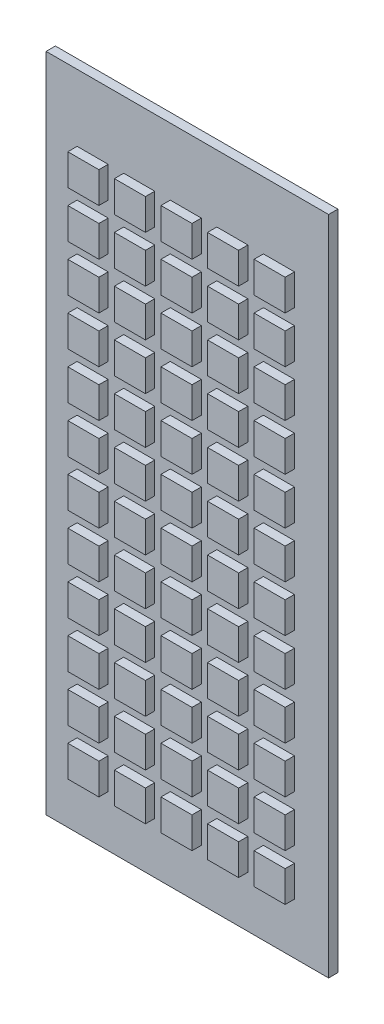
SolidWorks part; units mm, degrees
ref_plane "Alzado" through (0, 0, 0) normal (0, 0, 1) x (1, 0, 0)
ref_plane "Planta" through (0, 0, 0) normal (0, 1, 0) x (1, 0, 0)
ref_plane "Vista lateral" through (0, 0, 0) normal (1, 0, 0) x (0, 0, -1)
sketch "Croquis1" plane through (0, 0, 0) normal (0, 0, 1) x (1, 0, 0)
  line L1 (-455, -1065) -> (455, -1065)
  line L2 (-455, -1065) -> (-455, 1065)
  line L3 (-455, 1065) -> (455, 1065)
  line L4 (455, -1065) -> (455, 1065)
  line L5 (-455, -1065) -> (455, 1065) construction
  line L6 (-455, 1065) -> (455, -1065) construction
  point P0 (0, 0)
  dimension "D1" = 2130
  dimension "D2" = 910
extrude "Saliente-Extruir1" add sketch "Croquis1" along normal blind 30
sketch "Croquis2" plane through (0, 0, 30) normal (0, 0, 1) x (1, 0, 0)
  line L0 (-455, 1065) -> (-455, -1065) construction
  line L1 (-355, 850) -> (-255, 850)
  line L2 (-355, 850) -> (-355, 750)
  line L3 (-355, 750) -> (-255, 750)
  line L4 (-255, 850) -> (-255, 750)
  line L5 (-355, 850) -> (-255, 750) construction
  line L6 (-355, 750) -> (-255, 850) construction
  line L7 (-205, 850) -> (-105, 850)
  line L8 (-205, 850) -> (-205, 750)
  line L9 (-205, 750) -> (-105, 750)
  line L10 (-105, 850) -> (-105, 750)
  line L11 (-205, 850) -> (-105, 750) construction
  line L12 (-205, 750) -> (-105, 850) construction
  line L13 (-55, 850) -> (45, 850)
  line L14 (-55, 850) -> (-55, 750)
  line L15 (-55, 750) -> (45, 750)
  line L16 (45, 850) -> (45, 750)
  line L17 (-55, 850) -> (45, 750) construction
  line L18 (-55, 750) -> (45, 850) construction
  line L19 (95, 850) -> (195, 850)
  line L20 (95, 850) -> (95, 750)
  line L21 (95, 750) -> (195, 750)
  line L22 (195, 850) -> (195, 750)
  line L23 (95, 850) -> (195, 750) construction
  line L24 (95, 750) -> (195, 850) construction
  line L25 (245, 850) -> (345, 850)
  line L26 (245, 850) -> (245, 750)
  line L27 (245, 750) -> (345, 750)
  line L28 (345, 850) -> (345, 750)
  line L29 (245, 850) -> (345, 750) construction
  line L30 (245, 750) -> (345, 850) construction
  line L31 (-205, 700) -> (-105, 700)
  line L32 (-205, 700) -> (-205, 600)
  line L33 (-205, 600) -> (-105, 600)
  line L34 (-105, 700) -> (-105, 600)
  line L35 (-205, 700) -> (-105, 600) construction
  line L36 (-205, 600) -> (-105, 700) construction
  line L37 (-55, 700) -> (45, 700)
  line L38 (-55, 700) -> (-55, 600)
  line L39 (-55, 600) -> (45, 600)
  line L40 (45, 700) -> (45, 600)
  line L41 (-55, 700) -> (45, 600) construction
  line L42 (-55, 600) -> (45, 700) construction
  line L43 (95, 700) -> (195, 700)
  line L44 (95, 700) -> (95, 600)
  line L45 (95, 600) -> (195, 600)
  line L46 (195, 700) -> (195, 600)
  line L47 (95, 700) -> (195, 600) construction
  line L48 (95, 600) -> (195, 700) construction
  line L49 (245, 700) -> (345, 700)
  line L50 (245, 700) -> (245, 600)
  line L51 (245, 600) -> (345, 600)
  line L52 (345, 700) -> (345, 600)
  line L53 (245, 700) -> (345, 600) construction
  line L54 (245, 600) -> (345, 700) construction
  line L55 (-205, 550) -> (-105, 550)
  line L56 (-205, 550) -> (-205, 450)
  line L57 (-205, 450) -> (-105, 450)
  line L58 (-105, 550) -> (-105, 450)
  line L59 (-205, 550) -> (-105, 450) construction
  line L60 (-205, 450) -> (-105, 550) construction
  line L61 (-55, 550) -> (45, 550)
  line L62 (-55, 550) -> (-55, 450)
  line L63 (-55, 450) -> (45, 450)
  line L64 (45, 550) -> (45, 450)
  line L65 (-55, 550) -> (45, 450) construction
  line L66 (-55, 450) -> (45, 550) construction
  line L67 (95, 550) -> (195, 550)
  line L68 (95, 550) -> (95, 450)
  line L69 (95, 450) -> (195, 450)
  line L70 (195, 550) -> (195, 450)
  line L71 (95, 550) -> (195, 450) construction
  line L72 (95, 450) -> (195, 550) construction
  line L73 (245, 550) -> (345, 550)
  line L74 (245, 550) -> (245, 450)
  line L75 (245, 450) -> (345, 450)
  line L76 (345, 550) -> (345, 450)
  line L77 (245, 550) -> (345, 450) construction
  line L78 (245, 450) -> (345, 550) construction
  line L79 (-205, 400) -> (-105, 400)
  line L80 (-205, 400) -> (-205, 300)
  line L81 (-205, 300) -> (-105, 300)
  line L82 (-105, 400) -> (-105, 300)
  line L83 (-205, 400) -> (-105, 300) construction
  line L84 (-205, 300) -> (-105, 400) construction
  line L85 (-55, 400) -> (45, 400)
  line L86 (-55, 400) -> (-55, 300)
  line L87 (-55, 300) -> (45, 300)
  line L88 (45, 400) -> (45, 300)
  line L89 (-55, 400) -> (45, 300) construction
  line L90 (-55, 300) -> (45, 400) construction
  line L91 (95, 400) -> (195, 400)
  line L92 (95, 400) -> (95, 300)
  line L93 (95, 300) -> (195, 300)
  line L94 (195, 400) -> (195, 300)
  line L95 (95, 400) -> (195, 300) construction
  line L96 (95, 300) -> (195, 400) construction
  line L97 (245, 400) -> (345, 400)
  line L98 (245, 400) -> (245, 300)
  line L99 (245, 300) -> (345, 300)
  line L100 (345, 400) -> (345, 300)
  line L101 (245, 400) -> (345, 300) construction
  line L102 (245, 300) -> (345, 400) construction
  line L103 (-205, 250) -> (-105, 250)
  line L104 (-205, 250) -> (-205, 150)
  line L105 (-205, 150) -> (-105, 150)
  line L106 (-105, 250) -> (-105, 150)
  line L107 (-205, 250) -> (-105, 150) construction
  line L108 (-205, 150) -> (-105, 250) construction
  line L109 (-55, 250) -> (45, 250)
  line L110 (-55, 250) -> (-55, 150)
  line L111 (-55, 150) -> (45, 150)
  line L112 (45, 250) -> (45, 150)
  line L113 (-55, 250) -> (45, 150) construction
  line L114 (-55, 150) -> (45, 250) construction
  line L115 (95, 250) -> (195, 250)
  line L116 (95, 250) -> (95, 150)
  line L117 (95, 150) -> (195, 150)
  line L118 (195, 250) -> (195, 150)
  line L119 (95, 250) -> (195, 150) construction
  line L120 (95, 150) -> (195, 250) construction
  line L121 (245, 250) -> (345, 250)
  line L122 (245, 250) -> (245, 150)
  line L123 (245, 150) -> (345, 150)
  line L124 (345, 250) -> (345, 150)
  line L125 (245, 250) -> (345, 150) construction
  line L126 (245, 150) -> (345, 250) construction
  line L127 (-205, 100) -> (-105, 100)
  line L128 (-205, 100) -> (-205, 0)
  line L129 (-205, 0) -> (-105, 0)
  line L130 (-105, 100) -> (-105, 0)
  line L131 (-205, 100) -> (-105, 0) construction
  line L132 (-205, 0) -> (-105, 100) construction
  line L133 (-55, 100) -> (45, 100)
  line L134 (-55, 100) -> (-55, 0)
  line L135 (-55, 0) -> (45, 0)
  line L136 (45, 100) -> (45, 0)
  line L137 (-55, 100) -> (45, 0) construction
  line L138 (-55, 0) -> (45, 100) construction
  line L139 (95, 100) -> (195, 100)
  line L140 (95, 100) -> (95, 0)
  line L141 (95, 0) -> (195, 0)
  line L142 (195, 100) -> (195, 0)
  line L143 (95, 100) -> (195, 0) construction
  line L144 (95, 0) -> (195, 100) construction
  line L145 (245, 100) -> (345, 100)
  line L146 (245, 100) -> (245, 0)
  line L147 (245, 0) -> (345, 0)
  line L148 (345, 100) -> (345, 0)
  line L149 (245, 100) -> (345, 0) construction
  line L150 (245, 0) -> (345, 100) construction
  line L151 (-205, -50) -> (-105, -50)
  line L152 (-205, -50) -> (-205, -150)
  line L153 (-205, -150) -> (-105, -150)
  line L154 (-105, -50) -> (-105, -150)
  line L155 (-205, -50) -> (-105, -150) construction
  line L156 (-205, -150) -> (-105, -50) construction
  line L157 (-55, -50) -> (45, -50)
  line L158 (-55, -50) -> (-55, -150)
  line L159 (-55, -150) -> (45, -150)
  line L160 (45, -50) -> (45, -150)
  line L161 (-55, -50) -> (45, -150) construction
  line L162 (-55, -150) -> (45, -50) construction
  line L163 (95, -50) -> (195, -50)
  line L164 (95, -50) -> (95, -150)
  line L165 (95, -150) -> (195, -150)
  line L166 (195, -50) -> (195, -150)
  line L167 (95, -50) -> (195, -150) construction
  line L168 (95, -150) -> (195, -50) construction
  line L169 (245, -50) -> (345, -50)
  line L170 (245, -50) -> (245, -150)
  line L171 (245, -150) -> (345, -150)
  line L172 (345, -50) -> (345, -150)
  line L173 (245, -50) -> (345, -150) construction
  line L174 (245, -150) -> (345, -50) construction
  line L175 (-205, -200) -> (-105, -200)
  line L176 (-205, -200) -> (-205, -300)
  line L177 (-205, -300) -> (-105, -300)
  line L178 (-105, -200) -> (-105, -300)
  line L179 (-205, -200) -> (-105, -300) construction
  line L180 (-205, -300) -> (-105, -200) construction
  line L181 (-55, -200) -> (45, -200)
  line L182 (-55, -200) -> (-55, -300)
  line L183 (-55, -300) -> (45, -300)
  line L184 (45, -200) -> (45, -300)
  line L185 (-55, -200) -> (45, -300) construction
  line L186 (-55, -300) -> (45, -200) construction
  line L187 (95, -200) -> (195, -200)
  line L188 (95, -200) -> (95, -300)
  line L189 (95, -300) -> (195, -300)
  line L190 (195, -200) -> (195, -300)
  line L191 (95, -200) -> (195, -300) construction
  line L192 (95, -300) -> (195, -200) construction
  line L193 (245, -200) -> (345, -200)
  line L194 (245, -200) -> (245, -300)
  line L195 (245, -300) -> (345, -300)
  line L196 (345, -200) -> (345, -300)
  line L197 (245, -200) -> (345, -300) construction
  line L198 (245, -300) -> (345, -200) construction
  line L199 (-205, -350) -> (-105, -350)
  line L200 (-205, -350) -> (-205, -450)
  line L201 (-205, -450) -> (-105, -450)
  line L202 (-105, -350) -> (-105, -450)
  line L203 (-205, -350) -> (-105, -450) construction
  line L204 (-205, -450) -> (-105, -350) construction
  line L205 (-55, -350) -> (45, -350)
  line L206 (-55, -350) -> (-55, -450)
  line L207 (-55, -450) -> (45, -450)
  line L208 (45, -350) -> (45, -450)
  line L209 (-55, -350) -> (45, -450) construction
  line L210 (-55, -450) -> (45, -350) construction
  line L211 (95, -350) -> (195, -350)
  line L212 (95, -350) -> (95, -450)
  line L213 (95, -450) -> (195, -450)
  line L214 (195, -350) -> (195, -450)
  line L215 (95, -350) -> (195, -450) construction
  line L216 (95, -450) -> (195, -350) construction
  line L217 (245, -350) -> (345, -350)
  line L218 (245, -350) -> (245, -450)
  line L219 (245, -450) -> (345, -450)
  line L220 (345, -350) -> (345, -450)
  line L221 (245, -350) -> (345, -450) construction
  line L222 (245, -450) -> (345, -350) construction
  line L223 (-205, -500) -> (-105, -500)
  line L224 (-205, -500) -> (-205, -600)
  line L225 (-205, -600) -> (-105, -600)
  line L226 (-105, -500) -> (-105, -600)
  line L227 (-205, -500) -> (-105, -600) construction
  line L228 (-205, -600) -> (-105, -500) construction
  line L229 (-55, -500) -> (45, -500)
  line L230 (-55, -500) -> (-55, -600)
  line L231 (-55, -600) -> (45, -600)
  line L232 (45, -500) -> (45, -600)
  line L233 (-55, -500) -> (45, -600) construction
  line L234 (-55, -600) -> (45, -500) construction
  line L235 (95, -500) -> (195, -500)
  line L236 (95, -500) -> (95, -600)
  line L237 (95, -600) -> (195, -600)
  line L238 (195, -500) -> (195, -600)
  line L239 (95, -500) -> (195, -600) construction
  line L240 (95, -600) -> (195, -500) construction
  line L241 (245, -500) -> (345, -500)
  line L242 (245, -500) -> (245, -600)
  line L243 (245, -600) -> (345, -600)
  line L244 (345, -500) -> (345, -600)
  line L245 (245, -500) -> (345, -600) construction
  line L246 (245, -600) -> (345, -500) construction
  line L247 (-205, -650) -> (-105, -650)
  line L248 (-205, -650) -> (-205, -750)
  line L249 (-205, -750) -> (-105, -750)
  line L250 (-105, -650) -> (-105, -750)
  line L251 (-205, -650) -> (-105, -750) construction
  line L252 (-205, -750) -> (-105, -650) construction
  line L253 (-55, -650) -> (45, -650)
  line L254 (-55, -650) -> (-55, -750)
  line L255 (-55, -750) -> (45, -750)
  line L256 (45, -650) -> (45, -750)
  line L257 (-55, -650) -> (45, -750) construction
  line L258 (-55, -750) -> (45, -650) construction
  line L259 (95, -650) -> (195, -650)
  line L260 (95, -650) -> (95, -750)
  line L261 (95, -750) -> (195, -750)
  line L262 (195, -650) -> (195, -750)
  line L263 (95, -650) -> (195, -750) construction
  line L264 (95, -750) -> (195, -650) construction
  line L265 (245, -650) -> (345, -650)
  line L266 (245, -650) -> (245, -750)
  line L267 (245, -750) -> (345, -750)
  line L268 (345, -650) -> (345, -750)
  line L269 (245, -650) -> (345, -750) construction
  line L270 (245, -750) -> (345, -650) construction
  line L271 (-205, -800) -> (-105, -800)
  line L272 (-205, -800) -> (-205, -900)
  line L273 (-205, -900) -> (-105, -900)
  line L274 (-105, -800) -> (-105, -900)
  line L275 (-205, -800) -> (-105, -900) construction
  line L276 (-205, -900) -> (-105, -800) construction
  line L277 (-55, -800) -> (45, -800)
  line L278 (-55, -800) -> (-55, -900)
  line L279 (-55, -900) -> (45, -900)
  line L280 (45, -800) -> (45, -900)
  line L281 (-55, -800) -> (45, -900) construction
  line L282 (-55, -900) -> (45, -800) construction
  line L283 (95, -800) -> (195, -800)
  line L284 (95, -800) -> (95, -900)
  line L285 (95, -900) -> (195, -900)
  line L286 (195, -800) -> (195, -900)
  line L287 (95, -800) -> (195, -900) construction
  line L288 (95, -900) -> (195, -800) construction
  line L289 (245, -800) -> (345, -800)
  line L290 (245, -800) -> (245, -900)
  line L291 (245, -900) -> (345, -900)
  line L292 (345, -800) -> (345, -900)
  line L293 (245, -800) -> (345, -900) construction
  line L294 (245, -900) -> (345, -800) construction
  line L295 (-355, 700) -> (-255, 700)
  line L296 (-355, 700) -> (-355, 600)
  line L297 (-355, 600) -> (-255, 600)
  line L298 (-255, 700) -> (-255, 600)
  line L299 (-355, 700) -> (-255, 600) construction
  line L300 (-355, 600) -> (-255, 700) construction
  line L301 (-355, 550) -> (-255, 550)
  line L302 (-355, 550) -> (-355, 450)
  line L303 (-355, 450) -> (-255, 450)
  line L304 (-255, 550) -> (-255, 450)
  line L305 (-355, 550) -> (-255, 450) construction
  line L306 (-355, 450) -> (-255, 550) construction
  line L307 (-355, 400) -> (-255, 400)
  line L308 (-355, 400) -> (-355, 300)
  line L309 (-355, 300) -> (-255, 300)
  line L310 (-255, 400) -> (-255, 300)
  line L311 (-355, 400) -> (-255, 300) construction
  line L312 (-355, 300) -> (-255, 400) construction
  line L313 (-355, 250) -> (-255, 250)
  line L314 (-355, 250) -> (-355, 150)
  line L315 (-355, 150) -> (-255, 150)
  line L316 (-255, 250) -> (-255, 150)
  line L317 (-355, 250) -> (-255, 150) construction
  line L318 (-355, 150) -> (-255, 250) construction
  line L319 (-355, 100) -> (-255, 100)
  line L320 (-355, 100) -> (-355, 0)
  line L321 (-355, 0) -> (-255, 0)
  line L322 (-255, 100) -> (-255, 0)
  line L323 (-355, 100) -> (-255, 0) construction
  line L324 (-355, 0) -> (-255, 100) construction
  line L325 (-355, -50) -> (-255, -50)
  line L326 (-355, -50) -> (-355, -150)
  line L327 (-355, -150) -> (-255, -150)
  line L328 (-255, -50) -> (-255, -150)
  line L329 (-355, -50) -> (-255, -150) construction
  line L330 (-355, -150) -> (-255, -50) construction
  line L331 (-355, -200) -> (-255, -200)
  line L332 (-355, -200) -> (-355, -300)
  line L333 (-355, -300) -> (-255, -300)
  line L334 (-255, -200) -> (-255, -300)
  line L335 (-355, -200) -> (-255, -300) construction
  line L336 (-355, -300) -> (-255, -200) construction
  line L337 (-355, -350) -> (-255, -350)
  line L338 (-355, -350) -> (-355, -450)
  line L339 (-355, -450) -> (-255, -450)
  line L340 (-255, -350) -> (-255, -450)
  line L341 (-355, -350) -> (-255, -450) construction
  line L342 (-355, -450) -> (-255, -350) construction
  line L343 (-355, -500) -> (-255, -500)
  line L344 (-355, -500) -> (-355, -600)
  line L345 (-355, -600) -> (-255, -600)
  line L346 (-255, -500) -> (-255, -600)
  line L347 (-355, -500) -> (-255, -600) construction
  line L348 (-355, -600) -> (-255, -500) construction
  line L349 (-355, -650) -> (-255, -650)
  line L350 (-355, -650) -> (-355, -750)
  line L351 (-355, -750) -> (-255, -750)
  line L352 (-255, -650) -> (-255, -750)
  line L353 (-355, -650) -> (-255, -750) construction
  line L354 (-355, -750) -> (-255, -650) construction
  line L355 (-355, -800) -> (-255, -800)
  line L356 (-355, -800) -> (-355, -900)
  line L357 (-355, -900) -> (-255, -900)
  line L358 (-255, -800) -> (-255, -900)
  line L359 (-355, -800) -> (-255, -900) construction
  line L360 (-355, -900) -> (-255, -800) construction
  point P0 (-305, 800)
  point P11 (-155, 800)
  point P16 (-5, 800)
  point P21 (145, 800)
  point P26 (295, 800)
  point P31 (-155, 650)
  point P36 (-5, 650)
  point P41 (145, 650)
  point P46 (295, 650)
  point P51 (-155, 500)
  point P56 (-5, 500)
  point P61 (145, 500)
  point P66 (295, 500)
  point P71 (-155, 350)
  point P76 (-5, 350)
  point P81 (145, 350)
  point P86 (295, 350)
  point P91 (-155, 200)
  point P96 (-5, 200)
  point P101 (145, 200)
  point P106 (295, 200)
  point P111 (-155, 50)
  point P116 (-5, 50)
  point P121 (145, 50)
  point P126 (295, 50)
  point P131 (-155, -100)
  point P136 (-5, -100)
  point P141 (145, -100)
  point P146 (295, -100)
  point P151 (-155, -250)
  point P156 (-5, -250)
  point P161 (145, -250)
  point P166 (295, -250)
  point P171 (-155, -400)
  point P176 (-5, -400)
  point P181 (145, -400)
  point P186 (295, -400)
  point P191 (-155, -550)
  point P196 (-5, -550)
  point P201 (145, -550)
  point P206 (295, -550)
  point P211 (-155, -700)
  point P216 (-5, -700)
  point P221 (145, -700)
  point P226 (295, -700)
  point P231 (-155, -850)
  point P236 (-5, -850)
  point P241 (145, -850)
  point P246 (295, -850)
  point P251 (-305, 650)
  point P256 (-305, 500)
  point P261 (-305, 350)
  point P266 (-305, 200)
  point P271 (-305, 50)
  point P276 (-305, -100)
  point P281 (-305, -250)
  point P286 (-305, -400)
  point P291 (-305, -550)
  point P296 (-305, -700)
  point P301 (-305, -850)
  dimension "D1" = 100
  dimension "D2" = 800
  dimension "D3" = 100
  dimension "D4" = 5
  dimension "D5" = 12
extrude "Saliente-Extruir2" add sketch "Croquis2" along normal blind 30
